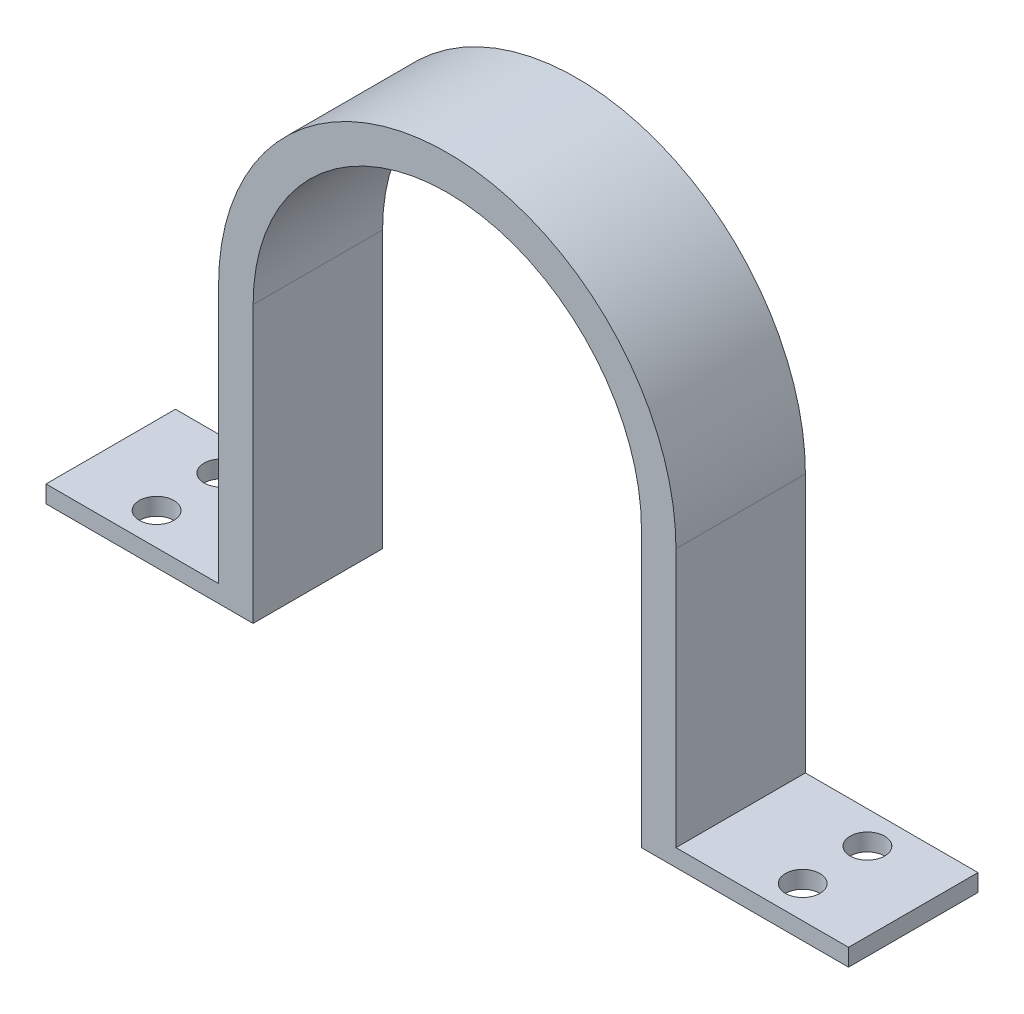
SolidWorks part; units mm, degrees
ref_plane "Front Plane" through (0, 0, 0) normal (0, 0, 1) x (1, 0, 0)
ref_plane "Top Plane" through (0, 0, 0) normal (0, 1, 0) x (1, 0, 0)
ref_plane "Right Plane" through (0, 0, 0) normal (1, 0, 0) x (0, 0, -1)
sketch "Sketch1" plane through (0, 0, 0) normal (0, 0, 1) x (1, 0, 0)
  line L0 (-22.5, 0) -> (22.5, 0)
  line L1 (26.5, 0) -> (26.5, 30)
  line L3 (-26.5, 30) -> (-26.5, 0)
  line L4 (-26.5, 0) -> (-46.5, 0)
  line L5 (-22.5, 30) -> (-22.5, 0)
  line L7 (22.5, 30) -> (22.5, 0)
  line L8 (-46.5, 0) -> (-46.5, -2)
  line L9 (-46.5, -2) -> (-22.5, -2)
  line L10 (-22.5, -2) -> (-22.5, 0)
  line L11 (26.5, 0) -> (46.5, 0)
  line L12 (46.5, 0) -> (46.5, -2)
  line L13 (46.5, -2) -> (22.5, -2)
  line L14 (22.5, -2) -> (22.5, 0)
  arc A0 (-26.5, 30) -> (26.5, 30) centre (0, 30) cw
  arc A1 (-22.5, 30) -> (22.5, 30) centre (0, 30) cw
  point P4 (0, 0)
  dimension "D4" = 30
  dimension "D1" = 4
  dimension "D2" = 4
  dimension "D3" = 45
  dimension "D5" = 2
  dimension "D6" = 2
  dimension "D7" = 24
  dimension "D8" = 24
extrude "Boss-Extrude1" add sketch "Sketch1" along normal blind 15 contours L5 A1 L7 L14 L13 L12 L11 L1 A0 L3 L4 L8 L9 L10
sketch "Sketch2" plane through (0, 0, 0) normal (0, 1, 0) x (1, 0, 0)
  line L2 (-26.5, 0) -> (-46.5, 0) construction
  line L3 (0, 6.247) -> (0, -4.4227) construction
  circle A0 centre (-37.435, -3.75) radius 2
  circle A1 centre (-37.435, -11.25) radius 2
  circle A2 centre (37.435, -11.25) radius 2
  circle A3 centre (37.435, -3.75) radius 2
  dimension "D1" = 4
  dimension "D2" = 7.5
  dimension "D3" = 3.75
extrude "Cut-Extrude1" cut sketch "Sketch2" against normal through all
